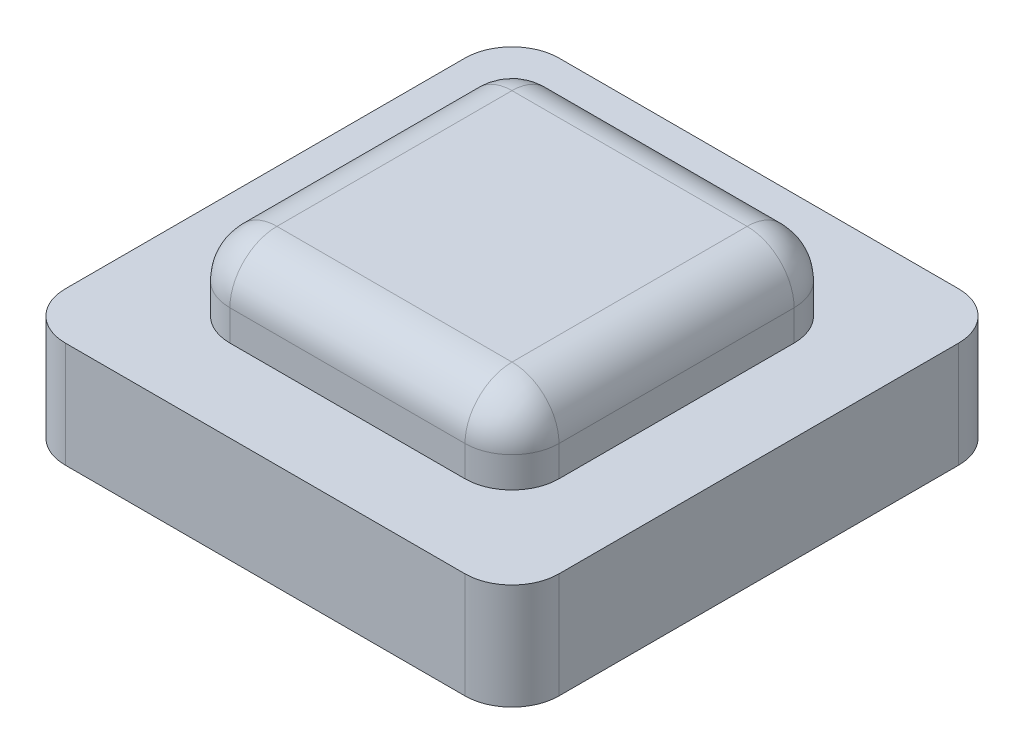
SolidWorks part; units mm, degrees
material "6063-T6"
ref_plane "Front Plane" through (0, 0, 0) normal (0, 0, 1) x (1, 0, 0)
ref_plane "Top Plane" through (0, 0, 0) normal (0, 1, 0) x (1, 0, 0)
ref_plane "Right Plane" through (0, 0, 0) normal (1, 0, 0) x (0, 0, -1)
sketch "Sketch1" plane through (0, 0, 0) normal (0, 1, 0) x (1, 0, 0)
  line L1 (-10.5, 10.5) -> (10.5, 10.5)
  line L2 (-10.5, 10.5) -> (-10.5, -10.5)
  line L3 (-10.5, -10.5) -> (10.5, -10.5)
  line L4 (10.5, 10.5) -> (10.5, -10.5)
  line L5 (-10.5, 10.5) -> (10.5, -10.5) construction
  line L6 (-10.5, -10.5) -> (10.5, 10.5) construction
  point P0 (0, 0)
  dimension "D1" = 21
extrude "Boss-Extrude1" add sketch "Sketch1" along normal blind 4.5
sketch "Sketch2" plane through (0, 0, 0) normal (0, -1, 0) x (1, 0, 0)
  line L1 (-4.75, 4.75) -> (4.75, 4.75)
  line L2 (-4.75, 4.75) -> (-4.75, -4.75)
  line L3 (-4.75, -4.75) -> (4.75, -4.75)
  line L4 (4.75, 4.75) -> (4.75, -4.75)
  line L5 (-4.75, 4.75) -> (4.75, -4.75) construction
  line L6 (-4.75, -4.75) -> (4.75, 4.75) construction
  point P0 (0, 0)
  dimension "D1" = 9.5
extrude "Boss-Extrude2" add sketch "Sketch2" along normal blind 3.5
sketch "Sketch3" plane through (0, 4.5, 0) normal (0, 1, 0) x (1, 0, 0)
  line L1 (-7, 7) -> (7, 7)
  line L2 (-7, 7) -> (-7, -7)
  line L3 (-7, -7) -> (7, -7)
  line L4 (7, 7) -> (7, -7)
  line L5 (-7, 7) -> (7, -7) construction
  line L6 (-7, -7) -> (7, 7) construction
  point P0 (0, 0)
  dimension "D1" = 14
extrude "Boss-Extrude3" add sketch "Sketch3" along normal blind 3.3
fillet "Fillet1" radius 2 4 edges at (-10.5, 2.25, -10.5) (10.5, 2.25, -10.5) (10.5, 2.25, 10.5) (-10.5, 2.25, 10.5)
fillet "Fillet2" radius 2 8 edges at (0, 7.8, 7) (7, 7.8, 0) (0, 7.8, -7) (-7, 7.8, 0) (-7, 6.15, 7) (-7, 6.15, -7) (7, 6.15, -7) (7, 6.15, 7)
fillet "Fillet3" radius 2 8 edges at (-4.75, -1.75, -4.75) (-4.75, -1.75, 4.75) (4.75, -1.75, 4.75) (4.75, -1.75, -4.75) (0, -3.5, -4.75) (-4.75, -3.5, 0) (0, -3.5, 4.75) (4.75, -3.5, 0)
equation "\"chip_size\"= 10mm"
equation "\"hold_edge\"= 1mm"
equation "\"holder_size\"= 32.2mm"
equation "\"M2P5\"= 2.5"
equation "\"height_SMA\"= 6.5"
equation "\"tube_SMA\"= 4mm"
equation "\"separation_SMA\"= 11"
equation "\"cavity_size\"=21"
equation "\"PCB_thickness\"= 0.51"
equation "\"PCB_Cu_thickness\"= 0.035"
equation "\"fillet_out\"= 3mm"
equation "\"fillet_cavity_top\"= 2"
equation "\"fillet_chip_sink\"= 0.4"
equation "\"fillet_cavity_bottom\"= 1"
equation "\"w_1\"= 1"
equation "\"s_1\"= 0.64"
equation "\"w_2\"= 0.6"
equation "\"s_2\"= 0.11"
equation "\"d_via\"= 0.25"
equation "\"D1@Sketch1\"=\"cavity_size\""
equation "\"D1@Sketch2\"=\"chip_size\"-0.5"
